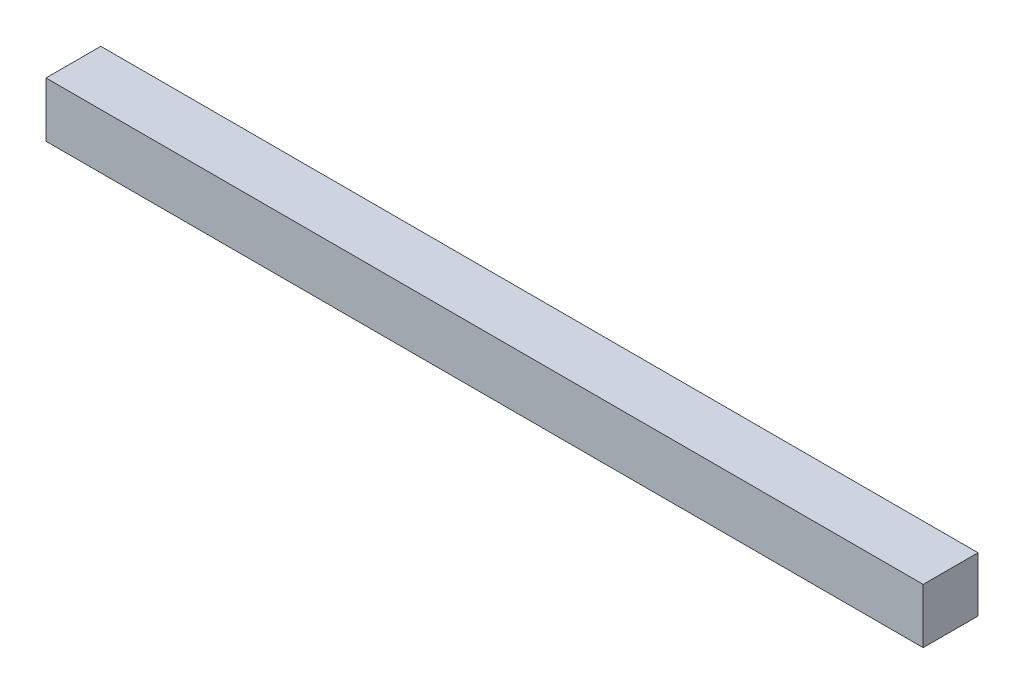
SolidWorks part; units mm, degrees
material "Plain Carbon Steel"
ref_plane "Front" through (0, 0, 0) normal (0, 0, 1) x (1, 0, 0)
ref_plane "Top" through (0, 0, 0) normal (0, 1, 0) x (1, 0, 0)
ref_plane "Right" through (0, 0, 0) normal (1, 0, 0) x (0, 0, -1)
sketch "Sketch1" plane through (0, 0, 0) normal (1, 0, 0) x (0, 0, -1)
  line L1 (-5, 5) -> (5, 5)
  line L2 (-5, 5) -> (-5, -5)
  line L3 (-5, -5) -> (5, -5)
  line L4 (5, 5) -> (5, -5)
  line L5 (-5, 5) -> (5, -5) construction
  line L6 (-5, -5) -> (5, 5) construction
  point P0 (0, 0)
  dimension "D1" = 10
extrude "Boss-Extrude1" add sketch "Sketch1" along normal mid plane 160
